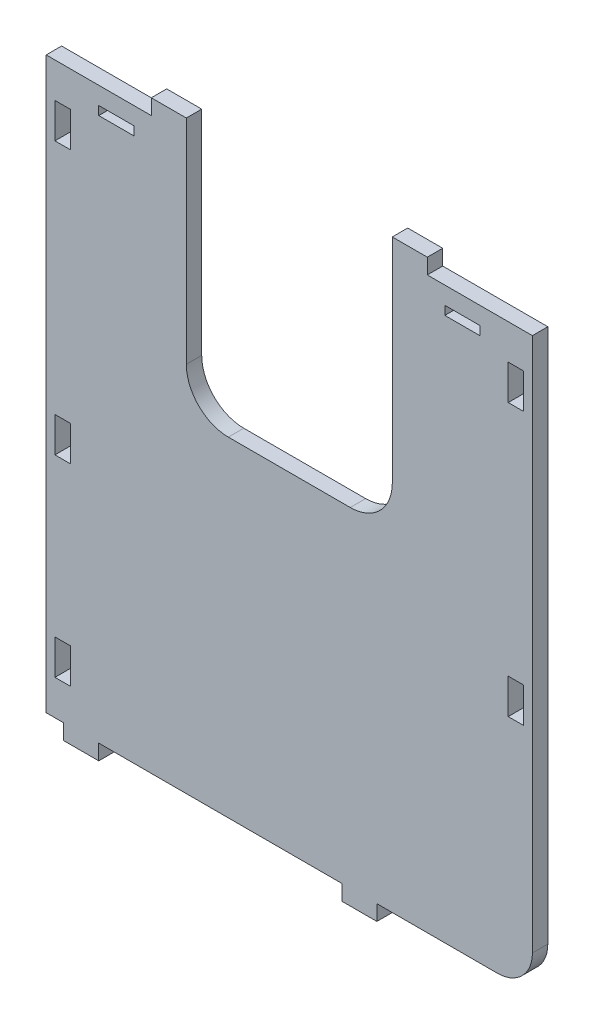
SolidWorks part; units mm, degrees
ref_plane "Front Plane" through (0, 0, 0) normal (0, 0, 1) x (1, 0, 0)
ref_plane "Top Plane" through (0, 0, 0) normal (0, 1, 0) x (1, 0, 0)
ref_plane "Right Plane" through (0, 0, 0) normal (1, 0, 0) x (0, 0, -1)
sketch "Sketch1" plane through (0, 0, 0) normal (0, 0, 1) x (1, 0, 0)
  line L0 (18.6626, 103.275) -> (-0.3874, 103.275)
  line L1 (-0.3874, 103.275) -> (-0.3874, 106.069)
  line L2 (-0.3874, 106.069) -> (-6.7374, 106.069)
  line L3 (-6.7374, 106.069) -> (-6.7374, 59.7823)
  line L4 (-50.4254, 103.275) -> (-69.4754, 103.275)
  line L5 (-69.4754, 103.275) -> (-69.4754, 0)
  line L6 (0, 0) -> (-50, 0) construction
  line L7 (-66.3004, 0) -> (-66.3004, -2.794)
  line L8 (-69.4754, -2.794) -> (-58.1089, -2.794) construction
  line L9 (-66.3004, -2.794) -> (-59.9504, -2.794)
  line L10 (-69.4754, 0) -> (-66.3004, 0)
  line L11 (18.6626, 0) -> (18.6626, 103.275)
  line L12 (-53.0289, -2.794) -> (-34.2964, -2.794) construction
  line L13 (17.0751, 90.575) -> (17.0751, 47.625) construction
  line L14 (17.0751, 103.275) -> (14.2811, 103.275) construction
  line L15 (-6.7374, 59.7823) -> (-44.0754, 59.7823)
  line L16 (-44.0754, 59.7823) -> (-44.0754, 106.069)
  line L17 (-44.0754, 106.069) -> (-50.4254, 106.069)
  line L18 (-50.4254, 106.069) -> (-50.4254, 103.275)
  line L20 (-59.9504, -2.794) -> (-59.9504, 0)
  line L21 (-15.8814, 0) -> (-15.8814, -2.794)
  line L22 (-4.1275, -2.794) -> (-16.5164, -2.794) construction
  line L23 (-15.8814, -2.794) -> (-9.5314, -2.794)
  line L24 (-9.5314, -2.794) -> (-9.5314, 0)
  line L25 (-59.9504, 0) -> (-15.8814, 0)
  line L26 (-9.5314, 0) -> (18.6626, 0)
  line L27 (-19.0564, -2.794) -> (-19.0564, 0) construction
  line L28 (-67.8879, 12.7) -> (-67.8879, 41.275) construction
  dimension "D1" = 1.5875
  dimension "D2" = 6.35
  dimension "D3" = 2.794
  dimension "D4" = 19.05
  dimension "D5" = 6.35
  dimension "D6" = 3.175
  dimension "D7" = 6.35
  dimension "D8" = 3.175
  dimension "D9" = 1.5875
extrude "Boss-Extrude1" add sketch "Sketch1" along normal blind 2.794 contours L10 L7 L9 L20 L25 L21 L23 L24 L26 L11 L0 L1 L2 L3 L15 L16 L17 L18 L4 L5
fillet "Fillet1" radius 7.62 2 edges at (-44.0754, 59.7823, 1.397) (-6.7374, 59.7823, 1.397)
sketch "Sketch2" plane through (0, 0, 2.794) normal (0, 0, 1) x (1, 0, 0)
  line L0 (-59.9504, 103.275) -> (-59.9504, 106.069) construction
  line L1 (-59.9504, 100.1) -> (-53.6004, 100.1)
  line L2 (-59.9504, 100.1) -> (-59.9504, 98.5125)
  line L3 (-59.9504, 98.5125) -> (-53.6004, 98.5125)
  line L4 (-53.6004, 100.1) -> (-53.6004, 98.5125)
  line L5 (2.7876, 100.1) -> (9.1376, 100.1)
  line L6 (2.7876, 100.1) -> (2.7876, 98.5125)
  line L7 (2.7876, 98.5125) -> (9.1376, 98.5125)
  line L8 (9.1376, 100.1) -> (9.1376, 98.5125)
  line L9 (-53.6004, 103.275) -> (-53.6004, 106.069) construction
  line L10 (-66.9354, 103.275) -> (16.1226, 103.275) construction
  line L11 (14.2811, 47.625) -> (14.2811, 41.275) construction
  line L12 (14.2811, 41.275) -> (17.0751, 41.275) construction
  line L13 (17.0751, 41.275) -> (17.0751, 47.625) construction
  line L14 (17.0751, 47.625) -> (14.2811, 47.625) construction
  line L15 (14.2811, 96.925) -> (14.2811, 90.575) construction
  line L16 (14.2811, 90.575) -> (17.0751, 90.575) construction
  line L17 (17.0751, 90.575) -> (17.0751, 96.925) construction
  line L18 (17.0751, 96.925) -> (14.2811, 96.925) construction
  line L19 (-65.0939, 90.575) -> (-65.0939, 96.925) construction
  line L20 (-65.0939, 96.925) -> (-67.8879, 96.925) construction
  line L21 (-67.8879, 96.925) -> (-67.8879, 90.575) construction
  line L22 (-67.8879, 90.575) -> (-65.0939, 90.575) construction
  line L23 (-65.0939, 41.275) -> (-65.0939, 47.625) construction
  line L24 (-65.0939, 47.625) -> (-67.8879, 47.625) construction
  line L25 (-67.8879, 47.625) -> (-67.8879, 41.275) construction
  line L26 (-67.8879, 41.275) -> (-65.0939, 41.275) construction
  line L27 (-65.0939, 6.35) -> (-65.0939, 12.7) construction
  line L28 (-65.0939, 12.7) -> (-67.8879, 12.7) construction
  line L29 (-67.8879, 12.7) -> (-67.8879, 6.35) construction
  line L30 (-67.8879, 6.35) -> (-65.0939, 6.35) construction
  line L31 (14.2811, 47.625) -> (14.2811, 41.275)
  line L32 (14.2811, 41.275) -> (17.0751, 41.275)
  line L33 (17.0751, 41.275) -> (17.0751, 47.625)
  line L34 (17.0751, 47.625) -> (14.2811, 47.625)
  line L35 (14.2811, 96.925) -> (14.2811, 90.575)
  line L36 (14.2811, 90.575) -> (17.0751, 90.575)
  line L37 (17.0751, 90.575) -> (17.0751, 96.925)
  line L38 (17.0751, 96.925) -> (14.2811, 96.925)
  line L39 (-65.0939, 90.575) -> (-65.0939, 96.925)
  line L40 (-65.0939, 96.925) -> (-67.8879, 96.925)
  line L41 (-67.8879, 96.925) -> (-67.8879, 90.575)
  line L42 (-67.8879, 90.575) -> (-65.0939, 90.575)
  line L43 (-65.0939, 41.275) -> (-65.0939, 47.625)
  line L44 (-65.0939, 47.625) -> (-67.8879, 47.625)
  line L45 (-67.8879, 47.625) -> (-67.8879, 41.275)
  line L46 (-67.8879, 41.275) -> (-65.0939, 41.275)
  line L47 (-65.0939, 6.35) -> (-65.0939, 12.7)
  line L48 (-65.0939, 12.7) -> (-67.8879, 12.7)
  line L49 (-67.8879, 12.7) -> (-67.8879, 6.35)
  line L50 (-67.8879, 6.35) -> (-65.0939, 6.35)
  dimension "D1" = 1.5875
  dimension "D2" = 3.175
  dimension "D3" = 6.35
  dimension "D4" = 3.175
  dimension "D5" = 1.5875
extrude "Cut-Extrude1" cut sketch "Sketch2" against normal through all
fillet "Fillet2" radius 6.35 1 edges at (18.6626, 0, 1.397)
equation "\"D1@Boss-Extrude1\"=\"thick@assy.sldasm\""
equation "\"D3@Sketch1\"=\"thick@assy.sldasm\""
